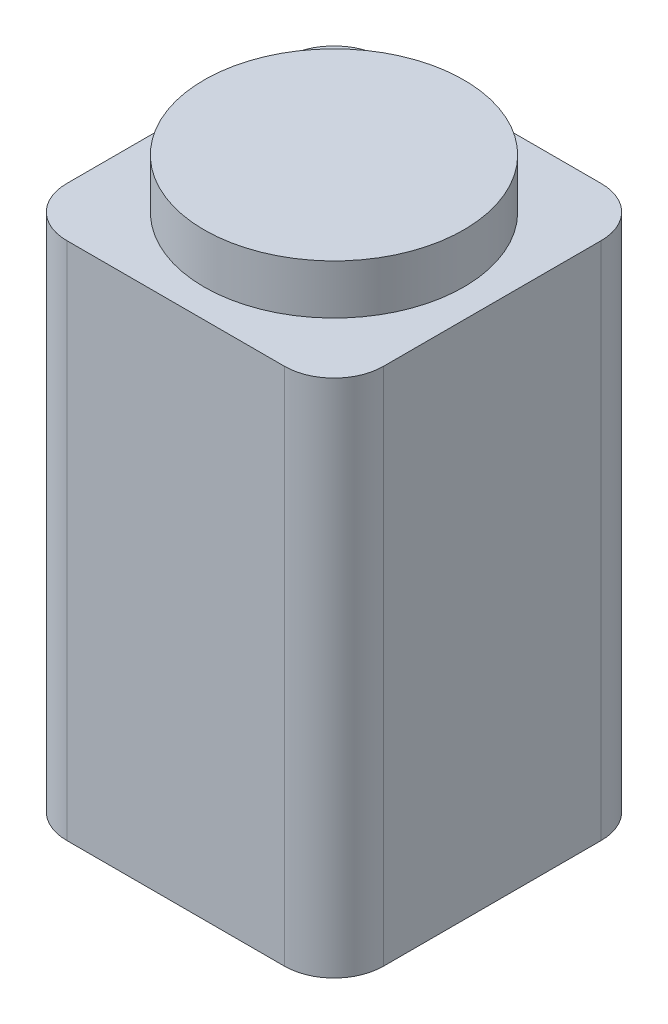
SolidWorks part; units mm, degrees
ref_plane "Front Plane" through (0, 0, 0) normal (0, 0, 1) x (1, 0, 0)
ref_plane "Top Plane" through (0, 0, 0) normal (0, 1, 0) x (1, 0, 0)
ref_plane "Right Plane" through (0, 0, 0) normal (1, 0, 0) x (0, 0, -1)
sketch "Sketch1" plane through (0, 0, 0) normal (0, 1, 0) x (1, 0, 0)
  line L1 (-20, 0) -> (-108, 0)
  line L2 (0, -20) -> (0, -108)
  line L3 (-20, -128) -> (-108, -128)
  line L4 (-128, -20) -> (-128, -108)
  arc A0 (-108, 0) -> (-128, -20) centre (-108, -20) ccw
  arc A1 (0, -20) -> (-20, 0) centre (-20, -20) ccw
  arc A2 (-20, -128) -> (0, -108) centre (-20, -108) ccw
  arc A3 (-128, -108) -> (-108, -128) centre (-108, -108) ccw
  point P7 (-128, 0)
  point P10 (0, 0)
  point P15 (-128, -128)
  dimension "D3" = 20
  dimension "D4" = 20
  dimension "D5" = 20
  dimension "D6" = 20
  dimension "D1" = 128
  dimension "D2" = 128
extrude "Boss-Extrude1" add sketch "Sketch1" along normal blind 210
sketch "Sketch2" plane through (0, 210, 0) normal (0, 1, 0) x (1, 0, 0)
  line L3 (-128, -20) -> (-128, -108) construction
  line L4 (-108, -128) -> (-20, -128) construction
  circle A0 centre (-64, -64) radius 52.5
  dimension "D3" = 105
  dimension "D1" = 64
  dimension "D2" = 64
extrude "Boss-Extrude2" add sketch "Sketch2" along normal blind 20 contours A0
